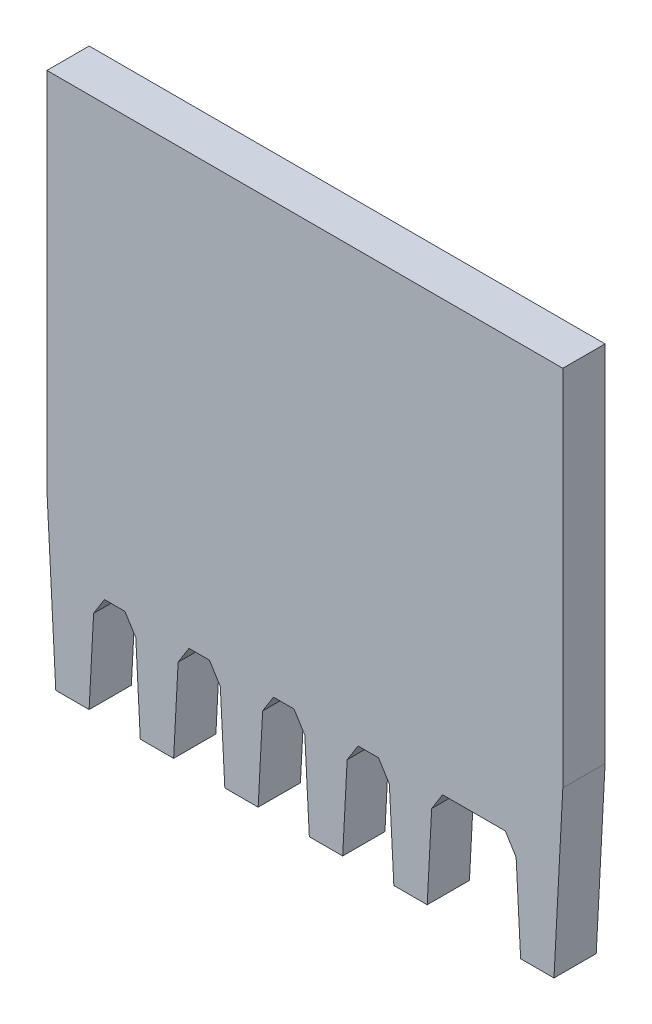
SolidWorks part; units mm, degrees
ref_plane "Front Plane" through (0, 0, 0) normal (0, 0, 1) x (1, 0, 0)
ref_plane "Top Plane" through (0, 0, 0) normal (0, 1, 0) x (1, 0, 0)
ref_plane "Right Plane" through (0, 0, 0) normal (1, 0, 0) x (0, 0, -1)
sketch "Sketch1" plane through (0, 0, 0) normal (0, 0, 1) x (1, 0, 0)
  line L0 (0, 0) -> (0, 18.9) construction
  line L1 (0, 18.9) -> (18.3124, 18.9) construction
  line L2 (18.3124, 18.9) -> (18.3124, 0) construction
  line L3 (18.3124, 0) -> (0, 0) construction
  line L4 (0, 3) -> (18.3124, 3) construction
  line L5 (0, 6) -> (18.3124, 6) construction
  line L6 (0.9062, 6) -> (0.9062, 0) construction
  line L7 (3.9062, 6) -> (3.9062, 0) construction
  line L8 (6.9062, 6) -> (6.9062, 0) construction
  line L9 (9.9062, 6) -> (9.9062, 0) construction
  line L10 (12.9062, 6) -> (12.9062, 0) construction
  line L11 (17.4062, 6) -> (17.4062, 0) construction
  line L12 (0.9062, 3) -> (3.9062, 3) construction
  line L13 (3.9062, 3) -> (6.9062, 3) construction
  line L14 (6.9062, 3) -> (9.9062, 3) construction
  line L15 (9.9062, 3) -> (12.9062, 3) construction
  line L16 (12.9062, 3) -> (17.4062, 3) construction
  line L17 (0.9062, 3) -> (0, 3) construction
  line L18 (17.4062, 3) -> (18.3124, 3) construction
  line L19 (2.4062, 3) -> (2.4062, 0) construction
  line L20 (5.4062, 3) -> (5.4062, 0) construction
  line L21 (8.4062, 3) -> (8.4062, 0) construction
  line L22 (11.4062, 3) -> (11.4062, 0) construction
  line L23 (15.1562, 3) -> (15.1562, 0) construction
  line L24 (14.4062, 3.75) -> (15.9062, 3.75) construction
  line L25 (0, 6) -> (0.3144, 0)
  line L26 (0.3144, 0) -> (1.4979, 0)
  line L27 (1.4979, 0) -> (1.6572, 3.0393)
  line L28 (3.1552, 3.0393) -> (3.3144, 0)
  line L29 (3.3144, 0) -> (4.4979, 0)
  line L30 (4.4979, 0) -> (4.6572, 3.0393)
  line L31 (6.1552, 3.0393) -> (6.3144, 0)
  line L32 (6.3144, 0) -> (7.4979, 0)
  line L33 (7.4979, 0) -> (7.6572, 3.0393)
  line L34 (9.1552, 3.0393) -> (9.3144, 0)
  line L35 (9.3144, 0) -> (10.4979, 0)
  line L36 (10.4979, 0) -> (10.6572, 3.0393)
  line L37 (12.1552, 3.0393) -> (12.3144, 0)
  line L38 (12.3144, 0) -> (13.4979, 0)
  line L39 (13.4979, 0) -> (13.6572, 3.0393)
  line L40 (16.6552, 3.0393) -> (16.8144, 0)
  line L41 (16.8144, 0) -> (17.9979, 0)
  line L42 (17.9979, 0) -> (18.3124, 6)
  line L44 (1.6572, 3.0393) -> (2.0426, 3.656)
  line L45 (0, 6) -> (0, 18.9)
  line L46 (0, 18.9) -> (18.3124, 18.9)
  line L47 (18.3124, 18.9) -> (18.3124, 6)
  line L48 (9.1562, 18.9) -> (9.1562, 6) construction
  line L49 (2.0426, 3.656) -> (2.7698, 3.656)
  line L50 (2.7698, 3.656) -> (3.1552, 3.0393)
  line L51 (4.6572, 3.0393) -> (5.0426, 3.656)
  line L52 (5.0426, 3.656) -> (5.7698, 3.656)
  line L53 (5.7698, 3.656) -> (6.1552, 3.0393)
  line L54 (7.6572, 3.0393) -> (8.0426, 3.656)
  line L55 (8.0426, 3.656) -> (8.7698, 3.656)
  line L56 (8.7698, 3.656) -> (9.1552, 3.0393)
  line L57 (10.6572, 3.0393) -> (11.0426, 3.656)
  line L58 (11.0426, 3.656) -> (11.7698, 3.656)
  line L59 (11.7698, 3.656) -> (12.1552, 3.0393)
  line L60 (13.6572, 3.0393) -> (14.0426, 3.656)
  line L61 (14.0426, 3.656) -> (16.2698, 3.656)
  line L62 (16.2698, 3.656) -> (16.6552, 3.0393)
  arc A0 (3.1552, 3.0393) -> (1.6572, 3.0393) centre (2.4062, 3) ccw construction
  arc A1 (6.1552, 3.0393) -> (4.6572, 3.0393) centre (5.4062, 3) ccw construction
  arc A2 (9.1552, 3.0393) -> (7.6572, 3.0393) centre (8.4062, 3) ccw construction
  arc A3 (12.1552, 3.0393) -> (10.6572, 3.0393) centre (11.4062, 3) ccw construction
  arc A4 (13.6572, 3.0393) -> (14.4062, 3.75) centre (14.4062, 3) cw construction
  arc A5 (16.6552, 3.0393) -> (15.9062, 3.75) centre (15.9062, 3) ccw construction
  dimension "D7" = 0.75
  dimension "D1" = 3
  dimension "D2" = 6
  dimension "D3" = 12.9
  dimension "D4" = 3
  dimension "D6" = 4.5
  dimension "D8" = 3
  dimension "D9" = 18.3124
  dimension "D10" = 18.9
extrude "Boss-Extrude1" add sketch "Sketch1" along normal blind 1.5
sketch "Sketch3" plane through (0, 0, 0) normal (0, 0, 1) x (1, 0, 0)
  line L0 (-0.4005, 6) -> (18.7129, 6)
  line L1 (18.7129, 3) -> (-0.4005, 3) construction
  line L2 (-0.4005, 0) -> (18.7129, 0) construction
  line L3 (-0.4005, -0.5) -> (18.7129, -0.5) construction
  line L4 (18.7129, -0.5) -> (18.7129, 6) construction
  line L5 (-0.4005, 6) -> (-0.4005, -0.5) construction
  line L6 (18.3124, 0) -> (0, 0) construction
  line L7 (0, 3) -> (18.3124, 3) construction
  line L8 (0, 6) -> (18.3124, 6) construction
  line L9 (0.3407, -0.5) -> (0, 6) construction
  line L10 (18.3124, 6) -> (17.9717, -0.5) construction
  line L11 (17.9979, 0) -> (18.3124, 6) construction
  line L12 (0, 6) -> (0.3144, 0) construction
  line L13 (5.4062, 6) -> (5.4062, -0.5) construction
  line L14 (3.9062, 6) -> (3.9062, -0.5) construction
  line L15 (5.4062, 3) -> (5.4062, 0) construction
  line L16 (3.1572, 3) -> (3.3407, -0.5) construction
  line L17 (2.7567, 3) -> (2.9401, -0.5)
  line L18 (3.1552, 3.0393) -> (3.3144, 0) construction
  line L19 (2.9401, -0.5) -> (4.8723, -0.5)
  line L20 (4.8723, -0.5) -> (5.0557, 3)
  line L21 (2.8484, 1.25) -> (3.2478, 1.2709) construction
  line L22 (5.9401, -0.5) -> (5.7567, 3)
  line L26 (7.8723, -0.5) -> (5.9401, -0.5)
  line L27 (8.0557, 3) -> (7.8723, -0.5)
  line L30 (2.4062, -0.5) -> (2.4062, 6) construction
  line L31 (2.4062, 3) -> (2.4062, 0) construction
  line L32 (8.4062, 6) -> (8.4062, -0.5) construction
  line L34 (11.4062, -0.5) -> (11.4062, 6) construction
  line L35 (15.1562, -0.5) -> (15.1562, 6) construction
  line L36 (8.4062, 3) -> (8.4062, 0) construction
  line L37 (11.4062, 3) -> (11.4062, 0) construction
  line L38 (15.1562, 3) -> (15.1562, 0) construction
  line L39 (10.8723, -0.5) -> (11.0557, 3)
  line L40 (8.9401, -0.5) -> (10.8723, -0.5)
  line L41 (8.7567, 3) -> (8.9401, -0.5)
  line L42 (11.9401, -0.5) -> (11.7567, 3)
  line L43 (13.8723, -0.5) -> (11.9401, -0.5)
  line L44 (14.0557, 3) -> (13.8723, -0.5)
  line L45 (16.4401, -0.5) -> (18.3723, -0.5)
  line L46 (16.2567, 3) -> (16.4401, -0.5)
  line L47 (18.3723, -0.5) -> (18.7129, 6)
  line L48 (1.8723, -0.5) -> (-0.0599, -0.5)
  line L49 (2.0557, 3) -> (1.8723, -0.5)
  line L50 (-0.0599, -0.5) -> (-0.4005, 6)
  line L51 (16.2567, 3) -> (14.0557, 3)
  line L52 (11.7567, 3) -> (11.0557, 3)
  line L53 (8.7567, 3) -> (8.0557, 3)
  line L54 (5.7567, 3) -> (5.0557, 3)
  line L55 (2.7567, 3) -> (2.0557, 3)
  dimension "D1" = 0.5
  dimension "D2" = 0.4
ref_plane "Plane1" through (3.9062, 0, 0) normal (1, 0, 0) x (0, 0, -1)
sketch "Sketch4" plane through (3.9062, 0, 0) normal (1, 0, 0) x (0, 0, -1)
  line L0 (0, 6) -> (0, -0.5) construction
  line L1 (0.6, 6) -> (-2.1, 6) construction
  line L2 (0.6, 6) -> (0.6, -0.5) construction
  line L3 (0.6, -0.5) -> (-2.1, -0.5) construction
  line L4 (-2.1, 6) -> (-2.1, -0.5) construction
  line L5 (-0.75, -0.5) -> (-0.75, 6) construction
  line L6 (-1.5, 6) -> (-1.5, -0.5) construction
  line L7 (0.6, 2.4005) -> (-2.1, 2.4005) construction
  line L8 (0.3, 6) -> (0.3, -0.5) construction
  line L9 (0.6, 2.4005) -> (3.846, 6) construction
  line L10 (2.2302, 6) -> (0.6, 4.1923) construction
  line L11 (0.6, 4.1923) -> (1.7139, 3.1878) construction
  line L12 (1.7139, 3.1878) -> (4.25, 6)
  line L13 (4.25, 6) -> (0.6, 6) construction
  line L14 (0.3, 1) -> (-1.8, 1) construction
  line L15 (-2.1, 0) -> (0.6, 0) construction
  line L16 (1.7139, 3.1878) -> (1.4912, 3.3887)
  line L17 (1.4912, 3.3887) -> (0.6, 2.4005)
  line L18 (-3.2139, 3.1878) -> (-5.75, 6)
  line L19 (-3.2139, 3.1878) -> (-2.9912, 3.3887)
  line L20 (-2.9912, 3.3887) -> (-2.1, 2.4005)
  line L21 (-2.1, 6) -> (-5.75, 6) construction
  line L22 (0.6, 3.0724) -> (3.2401, 6) construction
  arc A0 (0.4965, 2.2224) -> (0.6, -0.5) centre (4.2, 1) ccw
  arc A1 (0.6, 2.4005) -> (0.4965, 2.2224) centre (0.9713, 2.0656) ccw
  arc A2 (-2.1, 2.4005) -> (-1.9965, 2.2224) centre (-2.4713, 2.0656) cw
  arc A3 (-1.9965, 2.2224) -> (-2.1, -0.5) centre (-5.7, 1) cw
  dimension "D6" = 0.5
  dimension "D1" = 0.6
  dimension "D2" = 0.3
  dimension "D3" = 1.5
  dimension "D4" = 1
  dimension "D5" = 0.3
  dimension "D7" = 10
sketch "Sketch5" plane through (0, 0, 0) normal (1, 0, 0) x (0, 0, -1)
  line L0 (2.2302, 6) -> (0.6, 4.1923) construction
  line L1 (0.6, 4.1923) -> (1.7139, 3.1878) construction
  line L2 (1.7139, 3.1878) -> (4.25, 6) construction
  line L3 (2.2302, 6) -> (0.6, 4.1923) construction
  line L4 (0.6, 4.1923) -> (1.7139, 3.1878) construction
  line L5 (1.7139, 3.1878) -> (4.25, 6) construction
ref_plane "Plane2" through (0, 2.6105, -2.3541) normal (0, 0.7426, -0.6697) x (1, 0, 0)
sketch "Sketch6" plane through (0, 2.6105, -2.3541) normal (0, 0.7426, -0.6697) x (1, 0, 0)
  line L1 (3.9062, -2.362) -> (3.9062, -0.862) construction
  line L2 (3.9062, -2.362) -> (3.9062, -5.0612) construction
  line L3 (4.6562, -5.0612) -> (3.1562, -5.0612)
  line L4 (4.6562, -1.612) -> (3.1562, -1.612) construction
  line L5 (3.1562, -1.612) -> (3.1562, -5.0612)
  line L6 (4.6562, -1.612) -> (4.6562, -5.0612)
  line L10 (2.4062, -5.0612) -> (15.1562, -5.0612) construction
  line L11 (15.1562, -5.0612) -> (15.1562, -0.862) construction
  line L12 (15.1562, -0.862) -> (2.4062, -0.862) construction
  line L13 (2.4062, -0.862) -> (2.4062, -5.0612) construction
  line L14 (15.1562, 0.3349) -> (15.1562, -4.0182) construction
  line L15 (2.4062, 0.3349) -> (2.4062, -4.0182) construction
  line L16 (11.4062, -5.0612) -> (11.4062, -0.862) construction
  line L17 (8.4062, -5.0612) -> (8.4062, -0.862) construction
  line L18 (5.4062, -5.0612) -> (5.4062, -0.862) construction
  line L19 (5.4062, -4.0182) -> (5.4062, 0.3349) construction
  line L20 (8.4062, -4.0182) -> (8.4062, 0.3349) construction
  line L21 (11.4062, 0.3349) -> (11.4062, -4.0182) construction
  line L22 (0.1562, -1.612) -> (0.1562, -5.0612)
  line L23 (0.1562, -5.0612) -> (1.6562, -5.0612)
  line L24 (1.6562, -1.612) -> (1.6562, -5.0612)
  line L25 (7.6562, -1.612) -> (7.6562, -5.0612)
  line L26 (6.1562, -5.0612) -> (7.6562, -5.0612)
  line L27 (6.1562, -1.612) -> (6.1562, -5.0612)
  line L28 (10.6562, -1.612) -> (10.6562, -5.0612)
  line L29 (10.6562, -5.0612) -> (9.1562, -5.0612)
  line L30 (9.1562, -1.612) -> (9.1562, -5.0612)
  line L31 (13.6562, -1.612) -> (13.6562, -5.0612)
  line L32 (12.1562, -5.0612) -> (13.6562, -5.0612)
  line L33 (12.1562, -1.612) -> (12.1562, -5.0612)
  line L34 (18.1562, -1.612) -> (18.1562, -5.0612)
  line L35 (18.1562, -5.0612) -> (16.6562, -5.0612)
  line L36 (16.6562, -1.612) -> (16.6562, -5.0612)
  circle A0 centre (3.9062, -1.612) radius 0.75 construction
  arc A1 (4.6562, -1.612) -> (3.1562, -1.612) centre (3.9062, -1.612) ccw
  arc A2 (0.1562, -1.612) -> (1.6562, -1.612) centre (0.9062, -1.612) cw
  arc A3 (6.1562, -1.612) -> (7.6562, -1.612) centre (6.9062, -1.612) cw
  arc A4 (10.6562, -1.612) -> (9.1562, -1.612) centre (9.9062, -1.612) ccw
  arc A5 (12.1562, -1.612) -> (13.6562, -1.612) centre (12.9062, -1.612) cw
  arc A6 (18.1562, -1.612) -> (16.6562, -1.612) centre (17.4062, -1.612) ccw
ref_plane "Plane3" through (0, 1.6223, -1.463) normal (0, 0.7426, -0.6697) x (1, 0, 0)
sketch "Sketch7" plane through (0, 1.6223, -1.463) normal (0, 0.7426, -0.6697) x (1, 0, 0)
  line L0 (3.1562, -1.612) -> (3.1562, -5.0612) construction
  line L1 (4.6562, -5.0612) -> (3.1562, -5.0612) construction
  line L2 (4.6562, -1.612) -> (4.6562, -5.0612) construction
  line L3 (3.1562, -1.612) -> (3.1562, -5.0612) construction
  line L4 (4.6562, -5.0612) -> (3.1562, -5.0612) construction
  line L5 (4.6562, -1.612) -> (4.6562, -5.0612) construction
  line L6 (3.9062, -0.862) -> (3.9062, -5.0612) construction
  line L7 (4.6562, -1.612) -> (3.1562, -1.612) construction
  line L8 (4.6562, -2.362) -> (3.1562, -2.362) construction
  line L9 (3.4562, -1.612) -> (3.4562, -2.362)
  line L10 (3.4562, -2.362) -> (4.3562, -2.362)
  line L11 (4.3562, -2.362) -> (4.3562, -1.612)
  line L12 (2.4062, -0.862) -> (2.4062, -5.0612) construction
  line L13 (2.4062, -5.0612) -> (15.1562, -5.0612) construction
  line L14 (15.1562, -0.862) -> (2.4062, -0.862) construction
  line L15 (5.4062, -5.0612) -> (5.4062, -0.862) construction
  line L16 (8.4062, -5.0612) -> (8.4062, -0.862) construction
  line L17 (11.4062, -5.0612) -> (11.4062, -0.862) construction
  line L18 (15.1562, -5.0612) -> (15.1562, -0.862) construction
  line L19 (2.4062, -0.862) -> (2.4062, -5.0612) construction
  line L20 (2.4062, -5.0612) -> (15.1562, -5.0612) construction
  line L21 (15.1562, -0.862) -> (2.4062, -0.862) construction
  line L22 (5.4062, -5.0612) -> (5.4062, -0.862) construction
  line L23 (8.4062, -5.0612) -> (8.4062, -0.862) construction
  line L24 (11.4062, -5.0612) -> (11.4062, -0.862) construction
  line L25 (15.1562, -5.0612) -> (15.1562, -0.862) construction
  line L26 (0.4562, -2.362) -> (0.4562, -1.612)
  line L27 (1.3562, -2.362) -> (0.4562, -2.362)
  line L28 (1.3562, -1.612) -> (1.3562, -2.362)
  line L29 (7.3562, -2.362) -> (6.4562, -2.362)
  line L30 (7.3562, -1.612) -> (7.3562, -2.362)
  line L31 (6.4562, -2.362) -> (6.4562, -1.612)
  line L32 (9.4562, -1.612) -> (9.4562, -2.362)
  line L33 (10.3562, -2.362) -> (10.3562, -1.612)
  line L34 (9.4562, -2.362) -> (10.3562, -2.362)
  line L35 (13.3562, -1.612) -> (13.3562, -2.362)
  line L36 (12.4562, -2.362) -> (12.4562, -1.612)
  line L37 (13.3562, -2.362) -> (12.4562, -2.362)
  line L38 (16.9562, -1.612) -> (16.9562, -2.362)
  line L39 (17.8562, -2.362) -> (17.8562, -1.612)
  line L40 (16.9562, -2.362) -> (17.8562, -2.362)
  arc A0 (4.6562, -1.612) -> (3.1562, -1.612) centre (3.9062, -1.612) ccw construction
  arc A1 (4.6562, -1.612) -> (3.1562, -1.612) centre (3.9062, -1.612) ccw construction
  circle A2 centre (3.9062, -1.612) radius 0.45 construction
  arc A3 (4.3562, -1.612) -> (3.4562, -1.612) centre (3.9062, -1.612) ccw
  arc A4 (0.4562, -1.612) -> (1.3562, -1.612) centre (0.9062, -1.612) cw
  arc A5 (6.4562, -1.612) -> (7.3562, -1.612) centre (6.9062, -1.612) cw
  arc A6 (10.3562, -1.612) -> (9.4562, -1.612) centre (9.9062, -1.612) ccw
  arc A7 (12.4562, -1.612) -> (13.3562, -1.612) centre (12.9062, -1.612) cw
  arc A8 (17.8562, -1.612) -> (16.9562, -1.612) centre (17.4062, -1.612) ccw
ref_plane "bisect" through (0, 0, 0.75) normal (0, 0, 1) x (1, 0, 0)
ref_plane "insert_surface" through (0, 6, 0) normal (0, 1, 0) x (1, 0, 0)
sketch "Sketch8" plane through (0, 6, 0) normal (0, 1, 0) x (1, 0, 0)
  line L0 (18.7129, -0.75) -> (-0.4005, -0.75) construction
  line L1 (-0.4005, 0.6) -> (18.7129, 0.6)
  line L2 (-0.4005, 0.6) -> (-0.4005, -2.1)
  line L3 (-0.4005, -2.1) -> (18.7129, -2.1)
  line L4 (18.7129, 0.6) -> (18.7129, -2.1)
  line L5 (9.1562, 0.6) -> (9.1562, -2.1) construction
  line L6 (0, 0) -> (18.3124, 0) construction
  line L7 (0, 0) -> (0, -1.5) construction
  line L8 (0, -1.5) -> (18.3124, -1.5) construction
  line L9 (18.3124, 0) -> (18.3124, -1.5) construction
  line L10 (18.7129, 0.3) -> (-0.4005, 0.3) construction
  line L11 (18.7129, -1.8) -> (-0.4005, -1.8) construction
sketch "Sketch9" plane through (0, 0, 0) normal (0, 0, 1) x (1, 0, 0)
  line L0 (18.3723, -0.5) -> (18.7129, 6) construction
  line L1 (-0.4005, 6) -> (18.7129, 6) construction
  line L2 (-0.0599, -0.5) -> (-0.4005, 6) construction
  line L3 (1.8723, -0.5) -> (-0.0599, -0.5) construction
  line L4 (2.0557, 3) -> (1.8723, -0.5) construction
  line L5 (2.7567, 3) -> (2.0557, 3) construction
  line L6 (2.7567, 3) -> (2.9401, -0.5) construction
  line L7 (2.9401, -0.5) -> (4.8723, -0.5) construction
  line L8 (4.8723, -0.5) -> (5.0557, 3) construction
  line L9 (5.7567, 3) -> (5.0557, 3) construction
  line L10 (5.9401, -0.5) -> (5.7567, 3) construction
  line L11 (7.8723, -0.5) -> (5.9401, -0.5) construction
  line L12 (8.0557, 3) -> (7.8723, -0.5) construction
  line L13 (8.7567, 3) -> (8.0557, 3) construction
  line L14 (8.7567, 3) -> (8.9401, -0.5) construction
  line L15 (8.9401, -0.5) -> (10.8723, -0.5) construction
  line L16 (10.8723, -0.5) -> (11.0557, 3) construction
  line L17 (11.7567, 3) -> (11.0557, 3) construction
  line L18 (11.9401, -0.5) -> (11.7567, 3) construction
  line L19 (13.8723, -0.5) -> (11.9401, -0.5) construction
  line L20 (14.0557, 3) -> (13.8723, -0.5) construction
  line L21 (16.2567, 3) -> (14.0557, 3) construction
  line L22 (16.2567, 3) -> (16.4401, -0.5) construction
  line L23 (16.4401, -0.5) -> (18.3723, -0.5) construction
  line L24 (18.3723, -0.5) -> (18.7129, 6)
  line L25 (-0.4005, 6) -> (18.7129, 6) construction
  line L26 (-0.0599, -0.5) -> (-0.4005, 6)
  line L27 (1.8723, -0.5) -> (-0.0599, -0.5)
  line L28 (2.0557, 3) -> (1.8723, -0.5)
  line L29 (2.7567, 3) -> (2.0557, 3) construction
  line L30 (2.7567, 3) -> (2.9401, -0.5)
  line L31 (2.9401, -0.5) -> (4.8723, -0.5)
  line L32 (4.8723, -0.5) -> (5.0557, 3)
  line L33 (5.7567, 3) -> (5.0557, 3) construction
  line L34 (5.9401, -0.5) -> (5.7567, 3)
  line L35 (7.8723, -0.5) -> (5.9401, -0.5)
  line L36 (8.0557, 3) -> (7.8723, -0.5)
  line L37 (8.7567, 3) -> (8.0557, 3) construction
  line L38 (8.7567, 3) -> (8.9401, -0.5)
  line L39 (8.9401, -0.5) -> (10.8723, -0.5)
  line L40 (10.8723, -0.5) -> (11.0557, 3)
  line L41 (11.7567, 3) -> (11.0557, 3) construction
  line L42 (11.9401, -0.5) -> (11.7567, 3)
  line L43 (13.8723, -0.5) -> (11.9401, -0.5)
  line L44 (14.0557, 3) -> (13.8723, -0.5)
  line L45 (16.2567, 3) -> (14.0557, 3) construction
  line L46 (16.2567, 3) -> (16.4401, -0.5)
  line L47 (16.4401, -0.5) -> (18.3723, -0.5)
  line L48 (16.2567, 3) -> (16.2567, 6)
  line L49 (14.0557, 3) -> (14.0557, 6)
  line L50 (11.7567, 3) -> (11.7567, 6)
  line L51 (18.7129, 6) -> (-0.4005, 6) construction
  line L52 (11.0557, 3) -> (11.0557, 6)
  line L53 (-0.4005, 6) -> (18.7129, 6) construction
  line L54 (8.7567, 3) -> (8.7567, 6)
  line L55 (8.0557, 3) -> (8.0557, 6)
  line L58 (5.7567, 3) -> (5.7567, 6)
  line L60 (5.0557, 3) -> (5.0557, 6)
  line L62 (15.1562, -0.5) -> (15.1562, 6) construction
  line L63 (15.1562, -0.5) -> (15.1562, 6) construction
  line L64 (2.7567, 3) -> (2.7567, 6)
  line L65 (2.0557, 3) -> (2.0557, 6)
  line L67 (18.7129, 6) -> (16.2567, 6)
  line L68 (14.0557, 6) -> (11.7567, 6)
  line L69 (11.0557, 6) -> (8.7567, 6)
  line L70 (8.0557, 6) -> (5.7567, 6)
  line L71 (5.0557, 6) -> (2.7567, 6)
  line L72 (2.0557, 6) -> (-0.4005, 6)
